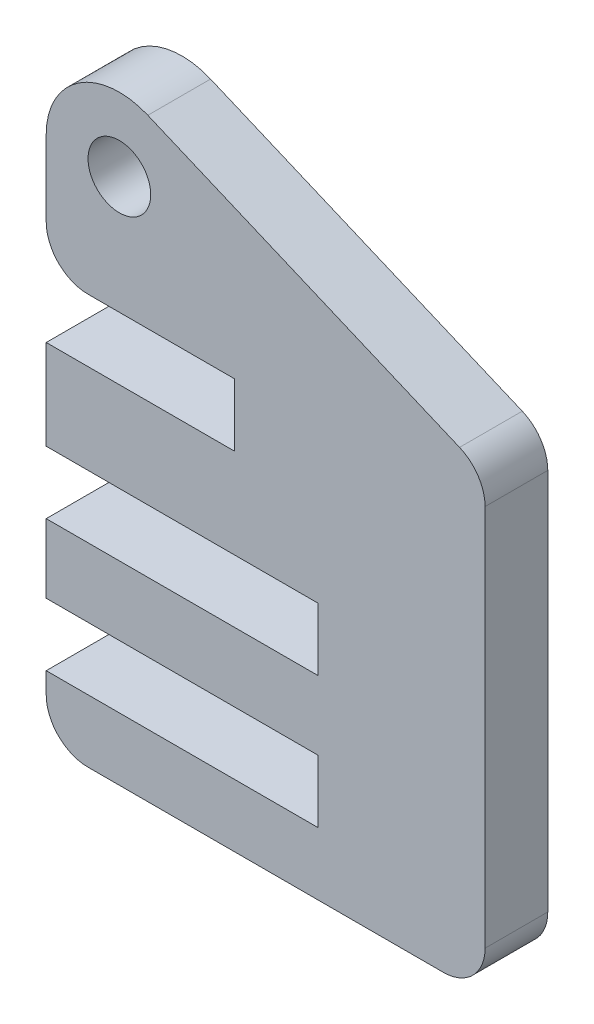
SolidWorks part; units mm, degrees
ref_plane "Front Plane" through (0, 0, 0) normal (0, 0, 1) x (1, 0, 0)
ref_plane "Top Plane" through (0, 0, 0) normal (0, 1, 0) x (1, 0, 0)
ref_plane "Right Plane" through (0, 0, 0) normal (1, 0, 0) x (0, 0, -1)
sketch "Sketch2" plane through (0, 0, 0) normal (0, 0, 1) x (1, 0, 0)
  line L1 (8.2506, 16.7916) -> (8.2506, -1.5084)
  line L2 (6.2506, -3.5084) -> (-10.7494, -3.5084)
  line L3 (-12.7494, -1.5084) -> (-12.7494, 21.7138)
  line L4 (7.0292, 18.6338) -> (-7.8869, 24.9377)
  arc A0 (7.0292, 18.6338) -> (8.2506, 16.7916) centre (6.2506, 16.7916) cw
  arc A1 (8.2506, -1.5084) -> (6.2506, -3.5084) centre (6.2506, -1.5084) cw
  arc A2 (-10.7494, -3.5084) -> (-12.7494, -1.5084) centre (-10.7494, -1.5084) cw
  arc A8 (-12.7494, 21.7138) -> (-7.8869, 24.9377) centre (-9.2494, 21.7138) cw
  dimension "D2" = 3.5
  dimension "D3" = 2
  dimension "D4" = 2
  dimension "D5" = 2
  dimension "D1" = 20.3
  dimension "D6" = 21
  dimension "D7" = 3.08
extrude "Boss-Extrude1" add sketch "Sketch2" along normal blind 3
sketch "Sketch4" plane through (0, 0, 3) normal (0, 0, 1) x (1, 0, 0)
  line L0 (-12.7494, 21.7138) -> (-12.7494, -1.5084) construction
  line L3 (-12.7494, 13.0916) -> (-3.7494, 13.0916)
  line L4 (-3.7494, 16.0916) -> (-3.7494, 13.0916)
  line L5 (-12.7494, 8.7916) -> (0.2506, 8.7916)
  line L6 (-12.7494, 8.7916) -> (-12.7494, 5.7916)
  line L7 (-12.7494, 5.7916) -> (0.2506, 5.7916)
  line L8 (0.2506, 8.7916) -> (0.2506, 5.7916)
  line L9 (8.2506, -1.5084) -> (8.2506, 16.7916) construction
  line L10 (-10.7494, -3.5084) -> (6.2506, -3.5084) construction
  line L11 (-12.7494, 2.4916) -> (0.2506, 2.4916)
  line L12 (-12.7494, 2.4916) -> (-12.7494, -0.5084)
  line L13 (-12.7494, -0.5084) -> (0.2506, -0.5084)
  line L14 (0.2506, 2.4916) -> (0.2506, -0.5084)
  line L15 (-3.7494, 16.0916) -> (-10.7494, 16.0916)
  line L16 (-12.7494, 21.7138) -> (-12.7494, -1.5084) construction
  line L17 (-12.7494, 18.0916) -> (-12.7494, 13.0916)
  arc A0 (-10.7494, 16.0916) -> (-12.7494, 18.0916) centre (-10.7494, 18.0916) cw
  dimension "D7" = 2
  dimension "D1" = 3
  dimension "D2" = 3
  dimension "D3" = 3
  dimension "D4" = 4.3
  dimension "D5" = 8
  dimension "D6" = 8
  dimension "D8" = 3
  dimension "D9" = 3.3
  dimension "D10" = 5
  dimension "D11" = 12
extrude "Cut-Extrude1" cut sketch "Sketch4" against normal blind 3
sketch "Sketch5" plane through (0, 0, 3) normal (0, 0, 1) x (1, 0, 0)
  circle A0 centre (-9.2494, 21.7138) radius 1.5
  arc A2 (-7.8869, 24.9377) -> (-12.7494, 21.7138) centre (-9.2494, 21.7138) ccw construction
  dimension "D1" = 3
extrude "Cut-Extrude2" cut sketch "Sketch5" against normal blind 3
